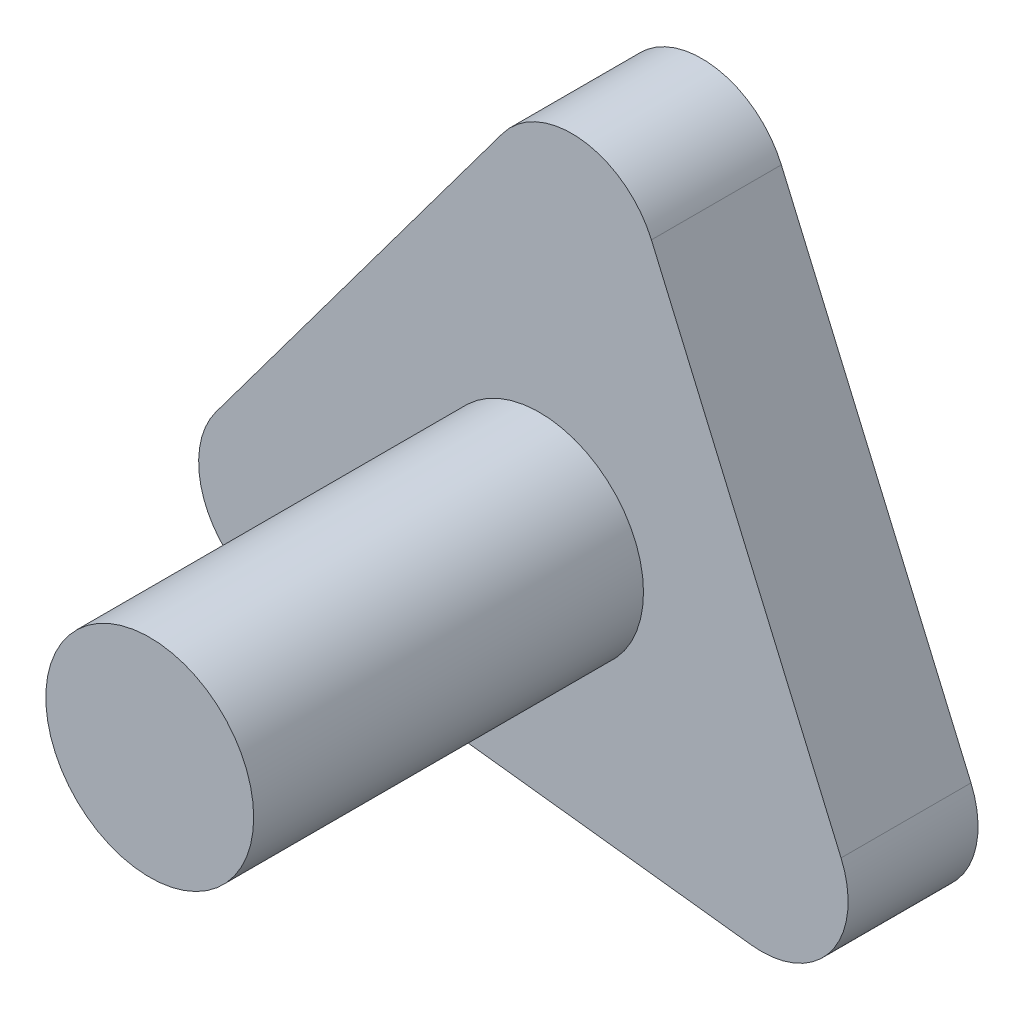
SolidWorks part; units mm, degrees
ref_plane "前视基准面" through (0, 0, 0) normal (0, 0, 1) x (1, 0, 0)
ref_plane "上视基准面" through (0, 0, 0) normal (0, 1, 0) x (1, 0, 0)
ref_plane "右视基准面" through (0, 0, 0) normal (1, 0, 0) x (0, 0, -1)
sketch "草图1" plane through (0, 0, 0) normal (0, 0, 1) x (1, 0, 0)
  circle A0 centre (0, 0) radius 2.4
extrude "凸台-拉伸1" add sketch "草图1" along normal blind 9
sketch "草图2" plane through (0, 0, 0) normal (0, 0, -1) x (-1, 0, 0)
  line L1 (9.5451, -4.11) -> (-1.2132, 10.3212)
  line L2 (-1.2132, 10.3212) -> (-8.3319, -6.2113)
  line L3 (-8.3319, -6.2113) -> (9.5451, -4.11)
  circle A0 centre (0, 0) radius 10.3923 construction
  dimension "D1" = 18
extrude "凸台-拉伸2" add sketch "草图2" along normal blind 3
fillet "圆角2" radius 2 1 edges at (-9.5451, -4.11, -1.5)
fillet "圆角3" radius 2 1 edges at (1.2132, 10.3212, -1.5)
fillet "圆角4" radius 2 1 edges at (8.3319, -6.2113, -1.5)
